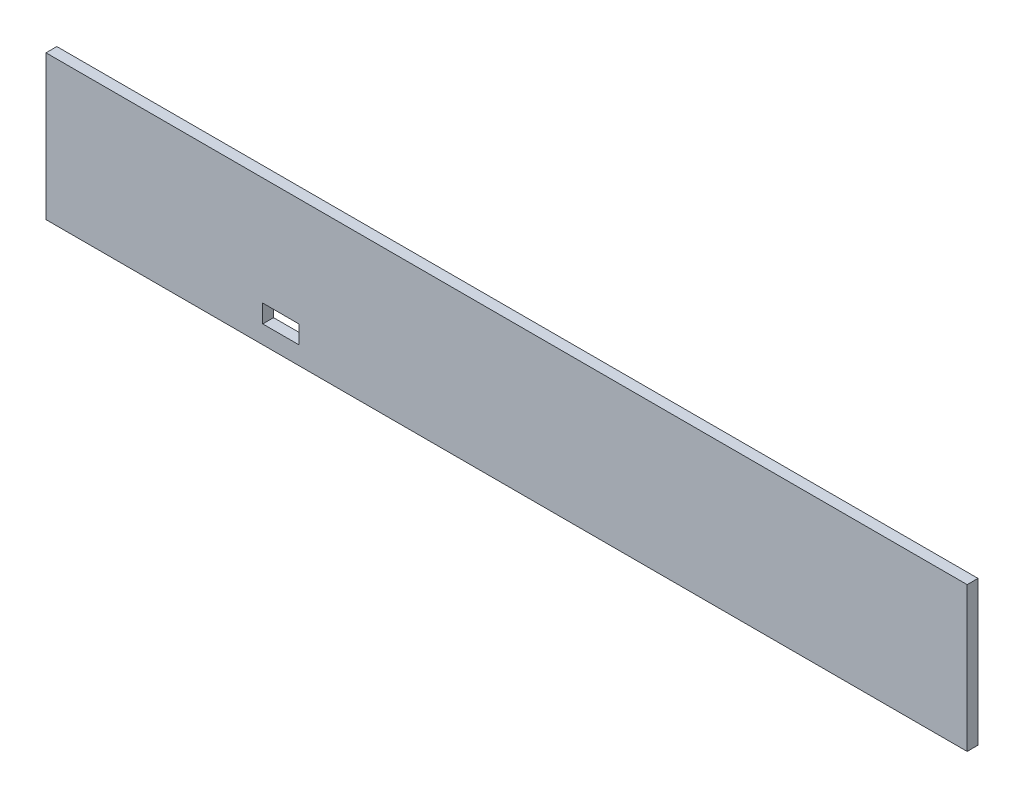
SolidWorks part; units mm, degrees
ref_plane "Front Plane" through (0, 0, 0) normal (0, 0, 1) x (1, 0, 0)
ref_plane "Top Plane" through (0, 0, 0) normal (0, 1, 0) x (1, 0, 0)
ref_plane "Right Plane" through (0, 0, 0) normal (1, 0, 0) x (0, 0, -1)
sketch "Sketch1" plane through (0, 0, 0) normal (0, 0, 1) x (1, 0, 0)
  line L1 (-61.6585, 21.1265) -> (193.3415, 21.1265)
  line L2 (-61.6585, 21.1265) -> (-61.6585, -18.8735)
  line L3 (-61.6585, -18.8735) -> (193.3415, -18.8735)
  line L4 (193.3415, 21.1265) -> (193.3415, -18.8735)
  line L5 (-1.6585, -8.8735) -> (8.3415, -8.8735)
  line L6 (-1.6585, -8.8735) -> (-1.6585, -13.8735)
  line L7 (-1.6585, -13.8735) -> (8.3415, -13.8735)
  line L8 (8.3415, -8.8735) -> (8.3415, -13.8735)
  point P8 (-1.6585, -11.3735)
  dimension "D1" = 40
  dimension "D2" = 255
  dimension "D3" = 60
  dimension "D4" = 70
  dimension "D5" = 5
  dimension "D6" = 5
extrude "Boss-Extrude1" add sketch "Sketch1" along normal blind 3
